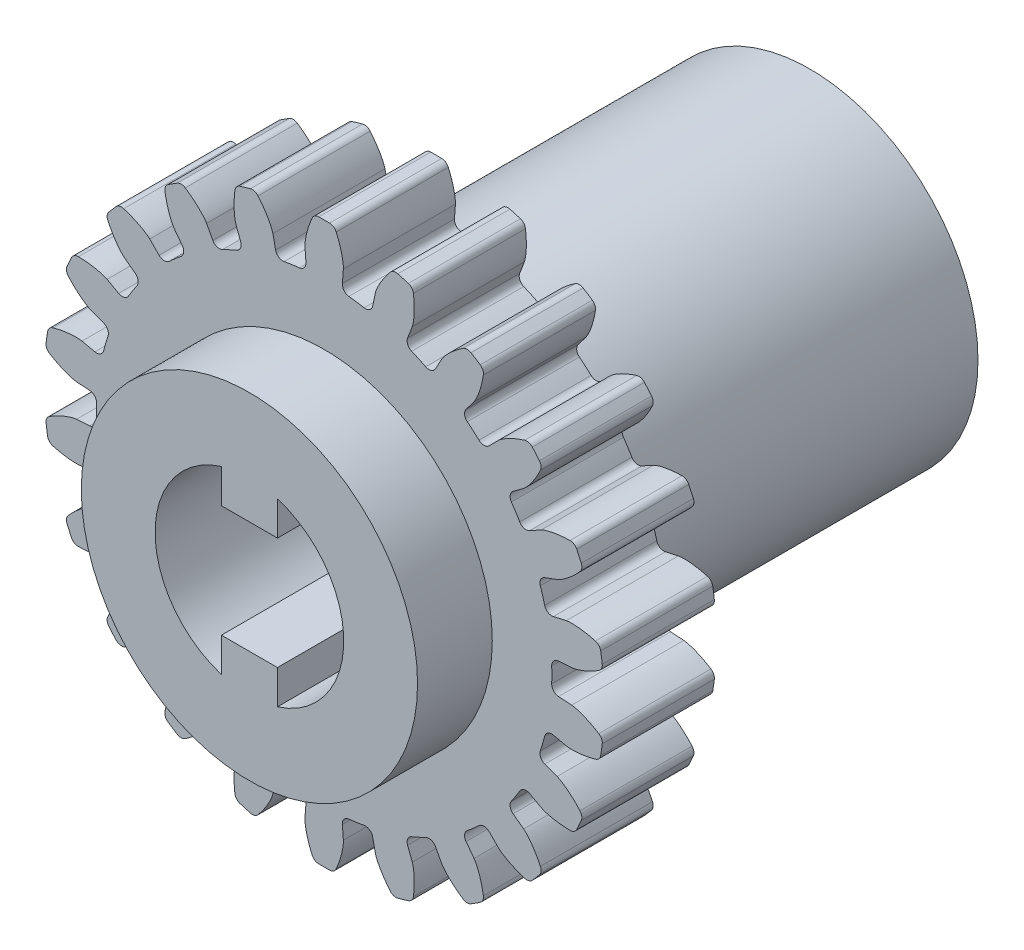
SolidWorks part; units mm, degrees
material "Brass"
ref_plane "Front Plane" through (0, 0, 0) normal (0, 0, 1) x (1, 0, 0)
ref_plane "Top Plane" through (0, 0, 0) normal (0, 1, 0) x (1, 0, 0)
ref_plane "Right Plane" through (0, 0, 0) normal (1, 0, 0) x (0, 0, -1)
sketch "Sketch1" plane through (0, 0, 0) normal (0, 0, 1) x (1, 0, 0)
  circle A0 centre (0, 0) radius 15
  dimension "D1" = 30
extrude "Boss-Extrude1" add sketch "Sketch1" along normal blind 6
sketch "Sketch2" plane through (0, 0, 6) normal (0, 0, 1) x (1, 0, 0)
  line L0 (13.2532, 0.866) -> (0, 0) construction
  line L1 (0, 0) -> (13.2532, -0.866) construction
  line L2 (12.1616, 0.7947) -> (13.2532, 0.866)
  line L3 (12.1616, -0.7947) -> (13.2532, -0.866)
  circle A0 centre (0, 0) radius 15 construction
  circle A1 centre (0, 0) radius 13.2815 construction
  circle A2 centre (0, 0) radius 13.75 construction
  circle A3 centre (0, 0) radius 12.1875 construction
  arc A4 (14.9146, 1.5987) -> (14.9146, -1.5987) centre (3.6281, 0) cw
  arc A5 (12.1616, -0.7947) -> (12.1616, 0.7947) centre (0, 0) ccw
  spline S0 degree 4 poles (13.2532, 0.866) (13.2559, 0.8662) (13.2635, 0.8669) (13.2777, 0.8685) (13.301, 0.8717) (13.3305, 0.8765) (13.3686, 0.8837) (13.4134, 0.8932) (13.4625, 0.9048) (13.5157, 0.9187) (13.5687, 0.9338) (13.6214, 0.9498) (13.6738, 0.9667) (13.7371, 0.9884) (13.8128, 1.0158) (13.9009, 1.0502) (14.0004, 1.0918) (14.1013, 1.1371) (14.2002, 1.1839) (14.2997, 1.2339) (14.3956, 1.2842) (14.4946, 1.3392) (14.5858, 1.3913) (14.6873, 1.4527) (14.7691, 1.5032) (14.8762, 1.5729) (14.9393, 1.6151) (15.0129, 1.6655) (15.0454, 1.6885) (15.0655, 1.7026) knots 0 0 0 0 0 0.005377 0.015084 0.028532 0.04661 0.064855 0.092111 0.119476 0.146842 0.174209 0.201575 0.228941 0.256307 0.307035 0.361767 0.4165 0.471232 0.525964 0.580697 0.635429 0.690161 0.744894 0.799626 0.854358 0.909091 0.954545 1 1 1 1 1 construction
  spline S1 degree 4 poles (13.2532, 0.866) (13.2559, 0.8662) (13.2635, 0.8669) (13.2777, 0.8685) (13.301, 0.8717) (13.3305, 0.8765) (13.3686, 0.8837) (13.4134, 0.8932) (13.4625, 0.9048) (13.5157, 0.9187) (13.5687, 0.9338) (13.6214, 0.9498) (13.6738, 0.9667) (13.7371, 0.9884) (13.8128, 1.0158) (13.9009, 1.0502) (14.0004, 1.0918) (14.1013, 1.1371) (14.2002, 1.1839) (14.2997, 1.2339) (14.3956, 1.2842) (14.4946, 1.3392) (14.5858, 1.3913) (14.6873, 1.4527) (14.7691, 1.5032) (14.853, 1.5578) (14.8938, 1.5848) (14.9146, 1.5987) knots 0 0 0 0 0 0.005377 0.015084 0.028532 0.04661 0.064855 0.092111 0.119476 0.146842 0.174209 0.201575 0.228941 0.256307 0.307035 0.361767 0.4165 0.471232 0.525964 0.580697 0.635429 0.690161 0.744894 0.799626 0.854358 0.909091 0.909091 0.909091 0.909091 0.909091
  spline S2 degree 4 poles (13.2532, -0.866) (13.2559, -0.8662) (13.2635, -0.8669) (13.2777, -0.8685) (13.301, -0.8717) (13.3305, -0.8765) (13.3686, -0.8837) (13.4134, -0.8932) (13.4625, -0.9048) (13.5157, -0.9187) (13.5687, -0.9338) (13.6214, -0.9498) (13.6738, -0.9667) (13.7371, -0.9884) (13.8128, -1.0158) (13.9009, -1.0502) (14.0004, -1.0918) (14.1013, -1.1371) (14.2002, -1.1839) (14.2997, -1.2339) (14.3956, -1.2842) (14.4946, -1.3392) (14.5858, -1.3913) (14.6873, -1.4527) (14.7691, -1.5032) (14.8762, -1.5729) (14.9393, -1.6151) (15.0129, -1.6655) (15.0454, -1.6885) (15.0655, -1.7026) knots 0 0 0 0 0 0.005377 0.015084 0.028532 0.04661 0.064855 0.092111 0.119476 0.146842 0.174209 0.201575 0.228941 0.256307 0.307035 0.361767 0.4165 0.471232 0.525964 0.580697 0.635429 0.690161 0.744894 0.799626 0.854358 0.909091 0.954545 1 1 1 1 1 construction
  spline S3 degree 4 poles (13.2532, -0.866) (13.2559, -0.8662) (13.2635, -0.8669) (13.2777, -0.8685) (13.301, -0.8717) (13.3305, -0.8765) (13.3686, -0.8837) (13.4134, -0.8932) (13.4625, -0.9048) (13.5157, -0.9187) (13.5687, -0.9338) (13.6214, -0.9498) (13.6738, -0.9667) (13.7371, -0.9884) (13.8128, -1.0158) (13.9009, -1.0502) (14.0004, -1.0918) (14.1013, -1.1371) (14.2002, -1.1839) (14.2997, -1.2339) (14.3956, -1.2842) (14.4946, -1.3392) (14.5858, -1.3913) (14.6873, -1.4527) (14.7691, -1.5032) (14.853, -1.5578) (14.8938, -1.5848) (14.9146, -1.5987) knots 0 0 0 0 0 0.005377 0.015084 0.028532 0.04661 0.064855 0.092111 0.119476 0.146842 0.174209 0.201575 0.228941 0.256307 0.307035 0.361767 0.4165 0.471232 0.525964 0.580697 0.635429 0.690161 0.744894 0.799626 0.854358 0.909091 0.909091 0.909091 0.909091 0.909091
  circle M4 centre (0, 0) radius 15
  dimension "D1" = 30
  dimension "D2" = 24.375
  dimension "D3" = 27.5
  dimension "D4" = 26.563
extrude "Cut-Extrude1" cut sketch "Sketch2" against normal through all contours L3 S3 S1 L2 A5 M4
sketch "Mate" plane through (0, 0, 0) normal (0, 0, 1) x (1, 0, 0)
  circle A0 centre (0, 0) radius 13.75
  circle A1 centre (0, 0) radius 13.75 construction
fillet "Fillet1" radius 0.3934 4 edges at (12.1616, -0.7947, 3) (12.1616, 0.7947, 3) (14.9146, -1.5987, 3) (14.9146, 1.5987, 3)
pattern_circular "CirPattern1" count 22 over 360 about axis through (0, 0, 0) along (0, 0, 1) of "Cut-Extrude1", "Fillet1"
sketch "Sketch4" plane through (0, 0, 0) normal (0, 0, 1) x (1, 0, 0)
  circle A0 centre (0, 0) radius 9
  dimension "D1" = 18
extrude "Boss-Extrude2" add sketch "Sketch4" against normal blind 20 and the other way blind 10
sketch "Sketch3" plane through (0, 0, 0) normal (0, 0, 1) x (1, 0, 0)
  line L0 (-1.5, 4.8221) -> (-1.5, 3)
  line L1 (-1.5, 3) -> (1.5, 3)
  line L2 (1.5, 3) -> (1.5, 4.8221)
  line L3 (1.5, -4.8221) -> (1.5, -3)
  line L4 (1.5, -3) -> (-1.5, -3)
  line L5 (-1.5, -3) -> (-1.5, -4.8221)
  circle A0 centre (0, 0) radius 5.05
  point P9 (0, 0)
  point P12 (0, 0)
  dimension "D1" = 10.1
  dimension "D2" = 3
  dimension "D3" = 6
extrude "Cut-Extrude2" cut sketch "Sketch3" along normal through all both and the other way through all contours L0 A0 L5 L4 L3 L2 L1
equation "\"DiametralPitch\"= 0.8"
equation "\"NumTeeth\"= 22"
equation "\"Addendum\"= 1 / \"DiametralPitch\""
equation "\"Dedendum\"= 1.25 / \"DiametralPitch\""
equation "\"WorkingDepth\"= 2 / \"DiametralPitch\""
equation "\"WholeDepth\"= 2.25 / \"DiametralPitch\""
equation "\"Clearance\"= 0.25 / \"DiametralPitch\""
equation "\"ToothThickness\"= 1.5708 / \"DiametralPitch\""
equation "\"CircularPitch\"= pi / \"DiametralPitch\""
equation "\"PitchCircle\"= \"NumTeeth\" / \"DiametralPitch\""
equation "\"OutsideDiameter\"= ( \"NumTeeth\" + 2 ) / \"DiametralPitch\""
equation "\"AddendumCircle\"= \"PitchCircle\" + ( 2 * \"Addendum\" )"
equation "\"DedendumCircle\"= \"PitchCircle\" - ( 2 * \"Dedendum\" )"
equation "\"PitchAngle\"= 360deg / \"NumTeeth\""
equation "\"PressureAngle\"= 15deg"
equation "\"Width\"= 6mm"
equation "\"Fillet\"= \"Clearance\" * cos ( \"PressureAngle\" ) * tan ( ( 90 + \"PressureAngle\" ) / 2 )"
equation "\"BaseCircle\"= \"PitchCircle\" * cos ( \"PressureAngle\" )"
equation "\"Alpha\"= sqr ( \"PitchCircle\" ^ 2 - \"BaseCircle\" ^ 2 ) / \"BaseCircle\" * 180 / PI - \"PressureAngle\""
equation "\"Beta\"= ( \"PitchAngle\" / 4 - \"Alpha\" )"
equation "\"Phi\"= sqr ( ( \"AddendumCircle\" / 2 ) ^ 2 - ( \"BaseCircle\" / 2 ) ^ 2 ) / ( \"BaseCircle\" / 2 )"
equation "\"D1@Sketch1\"=\"OutsideDiameter\""
equation "\"D1@Boss-Extrude1\"=\"Width\""
equation "\"D1@Sketch2\"=\"OutsideDiameter\""
equation "\"D2@Sketch2\"=\"DedendumCircle\""
equation "\"D3@Sketch2\"=\"PitchCircle\""
equation "\"D4@Sketch2\"=\"BaseCircle\""
equation "\"D1@Fillet1\"=\"Fillet\""
equation "\"D1@CirPattern1\"=\"NumTeeth\""
